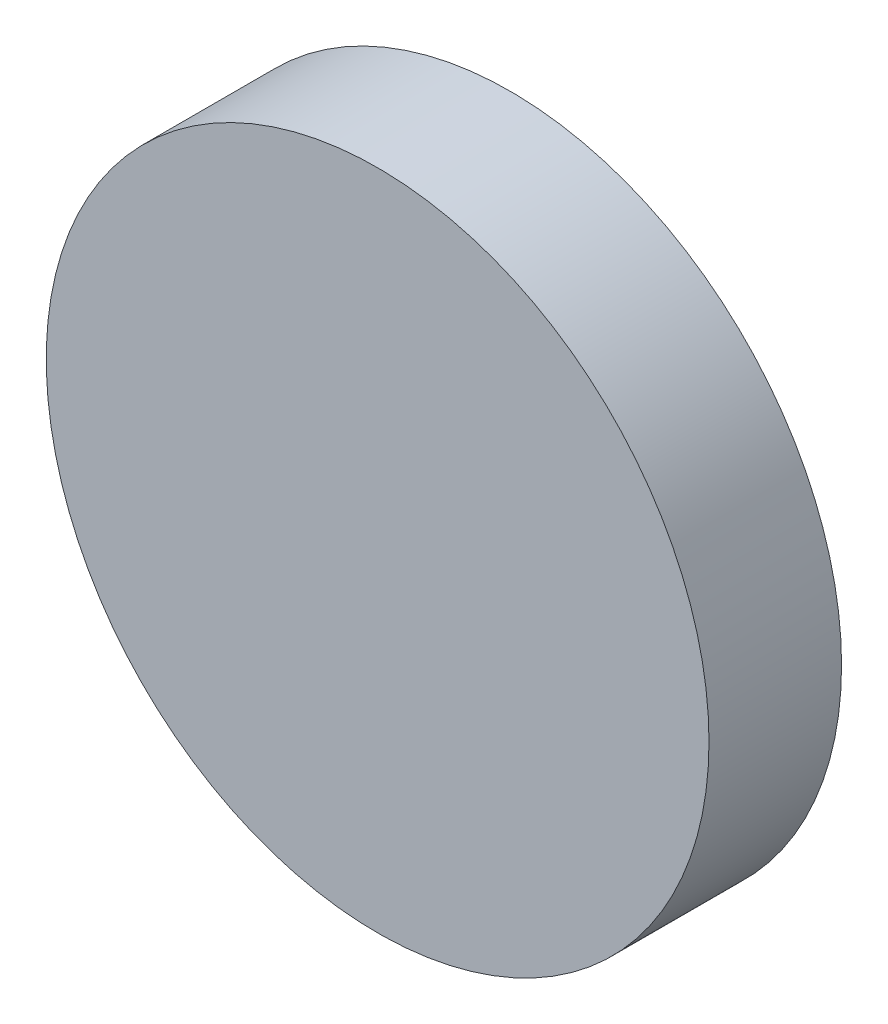
SolidWorks part; units mm, degrees
ref_plane "Front Plane" through (0, 0, 0) normal (0, 0, 1) x (1, 0, 0)
ref_plane "Top Plane" through (0, 0, 0) normal (0, 1, 0) x (1, 0, 0)
ref_plane "Right Plane" through (0, 0, 0) normal (1, 0, 0) x (0, 0, -1)
sketch "Sketch1" plane through (0, 0, 0) normal (0, 0, 1) x (1, 0, 0)
  circle A0 centre (0, 0) radius 75
extrude "Boss-Extrude1" add sketch "Sketch1" along normal blind 30
